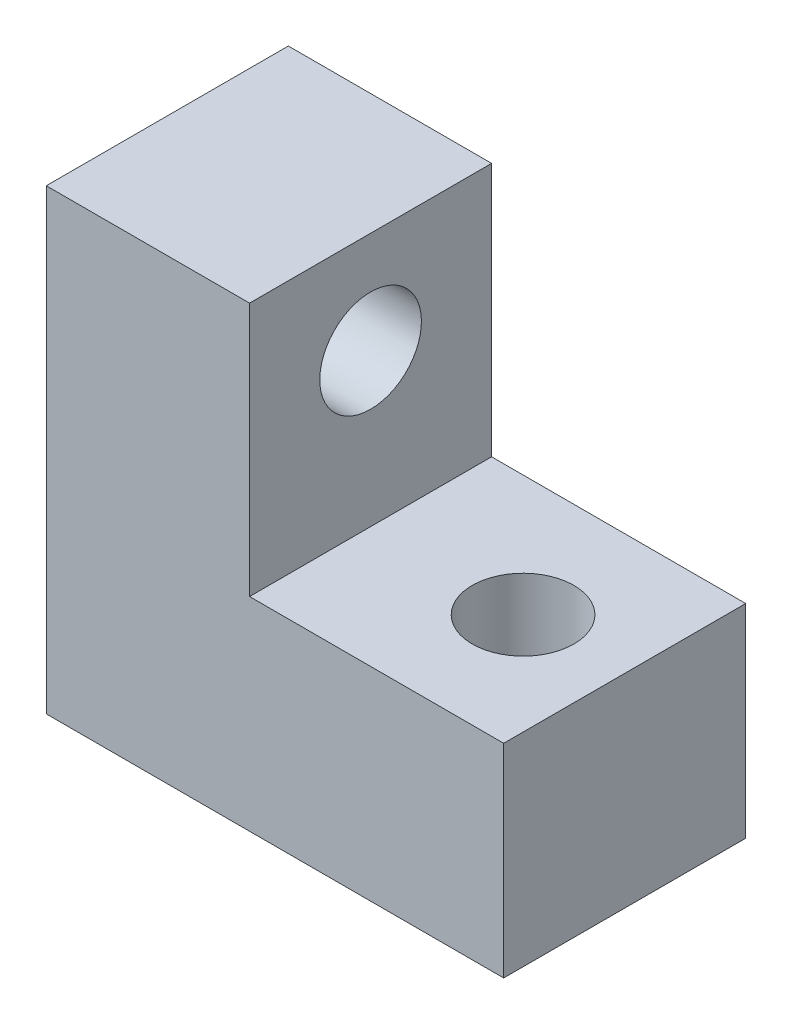
SolidWorks part; units mm, degrees
material "6061 Alloy"
ref_plane "Front Plane" through (0, 0, 0) normal (0, 0, 1) x (1, 0, 0)
ref_plane "Top Plane" through (0, 0, 0) normal (0, 1, 0) x (1, 0, 0)
ref_plane "Right Plane" through (0, 0, 0) normal (1, 0, 0) x (0, 0, -1)
sketch "Sketch1" plane through (0, 0, 0) normal (0, 0, 1) x (1, 0, 0)
  line L0 (9, 9) -> (0, 0) construction
  line L1 (0, 0) -> (18, 0)
  line L2 (0, 0) -> (0, 18)
  line L3 (0, 18) -> (18, 18) construction
  line L4 (18, 0) -> (18, 18) construction
  line L5 (9, 18) -> (9, 0) construction
  line L6 (0, 9) -> (18, 9) construction
  line L7 (0, 18) -> (8, 18)
  line L8 (8, 18) -> (8, 8)
  line L9 (8, 8) -> (18, 8)
  line L10 (18, 8) -> (18, 0)
  point P172 (9, 9)
  dimension "D1" = 8
  dimension "D2" = 18
extrude "3/8" add sketch "Sketch1" along normal blind 9.525
sketch "Sketch2" plane through (0, 0, 0) normal (-1, 0, 0) x (0, 0, 1)
  line L0 (4.7625, 18) -> (4.7625, 14) construction
  line L1 (9.525, 18) -> (0, 18) construction
  circle A0 centre (4.7625, 14) radius 2
  dimension "D1" = 4
  dimension "D2" = 4
extrude "M4_DRILL" cut sketch "Sketch2" against normal up to surface (8 mm away) up to face at (8, 13, 4.7625)
sketch "Sketch3" plane through (0, 0, 0) normal (0, -1, 0) x (-1, 0, 0)
  line L0 (-18, -4.7625) -> (-14, -4.7625) construction
  line L2 (-18, -9.525) -> (-18, 0) construction
  circle A0 centre (-14, -4.7625) radius 2
  dimension "D1" = 4
  dimension "D2" = 4
extrude "M4_DRILL2" cut sketch "Sketch3" against normal up to surface (8 mm away) up to face at (13, 8, 4.7625)
